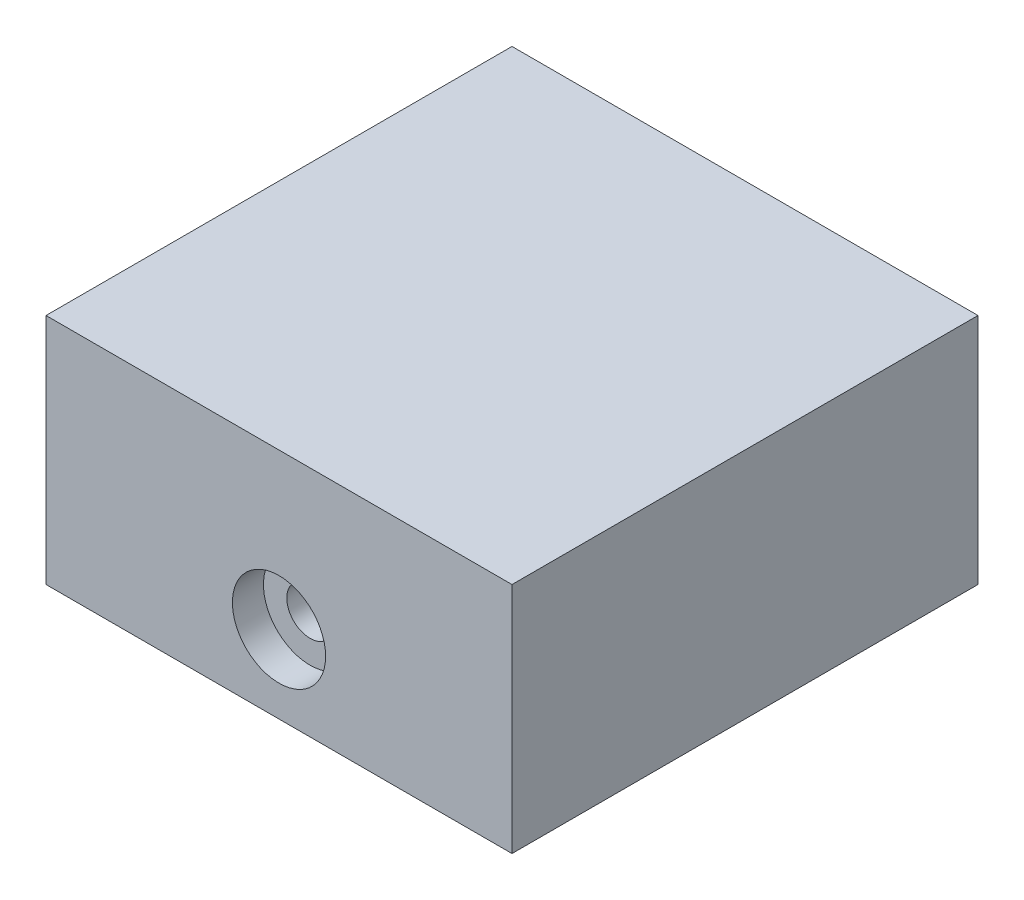
SolidWorks part; units mm, degrees
ref_plane "Front Plane" through (0, 0, 0) normal (0, 0, 1) x (1, 0, 0)
ref_plane "Top Plane" through (0, 0, 0) normal (0, 1, 0) x (1, 0, 0)
ref_plane "Right Plane" through (0, 0, 0) normal (1, 0, 0) x (0, 0, -1)
sketch "Sketch1" plane through (0, 0, 0) normal (0, 1, 0) x (1, 0, 0)
  line L1 (-15, 15) -> (15, 15)
  line L2 (-15, 15) -> (-15, -15)
  line L3 (-15, -15) -> (15, -15)
  line L4 (15, 15) -> (15, -15)
  line L5 (-15, 15) -> (15, -15) construction
  line L6 (-15, -15) -> (15, 15) construction
  point P0 (0, 0)
  dimension "D1" = 30
  dimension "D2" = 30
extrude "Boss-Extrude1" add sketch "Sketch1" along normal blind 15
sketch "Sketch2" plane through (0, 0, 0) normal (0, -1, 0) x (1, 0, 0)
  line L1 (10, 10) -> (-10, 10)
  line L2 (10, 10) -> (10, -10)
  line L3 (10, -10) -> (-10, -10)
  line L4 (-10, 10) -> (-10, -10)
  line L5 (10, 10) -> (-10, -10) construction
  line L6 (10, -10) -> (-10, 10) construction
  point P0 (0, 0)
  dimension "D1" = 20
  dimension "D2" = 20
extrude "Cut-Extrude1" cut sketch "Sketch2" against normal blind 10
sketch "Sketch3" plane through (0, 0, -15) normal (0, 0, -1) x (-1, 0, 0)
  line L0 (0, 0) -> (0, 10) construction
  circle A0 centre (0, 5) radius 1.5
  dimension "D1" = 10
extrude "Cut-Extrude2" cut sketch "Sketch3" against normal blind 30
sketch "Sketch4" plane through (0, 0, -15) normal (0, 0, -1) x (-1, 0, 0)
  line L1 (0, 2.0708) -> (2.5368, 3.5354)
  line L2 (2.5368, 3.5354) -> (2.5368, 6.4646)
  line L3 (2.5368, 6.4646) -> (0, 7.9292)
  line L4 (0, 7.9292) -> (-2.5368, 6.4646)
  line L5 (-2.5368, 6.4646) -> (-2.5368, 3.5354)
  line L6 (-2.5368, 3.5354) -> (0, 2.0708)
  circle A0 centre (0, 5) radius 2.5368 construction
extrude "Cut-Extrude3" cut sketch "Sketch4" against normal blind 2
sketch "Sketch5" plane through (0, 0, 15) normal (0, 0, 1) x (1, 0, 0)
  circle A0 centre (0, 5) radius 3
extrude "Cut-Extrude4" cut sketch "Sketch5" against normal blind 2
